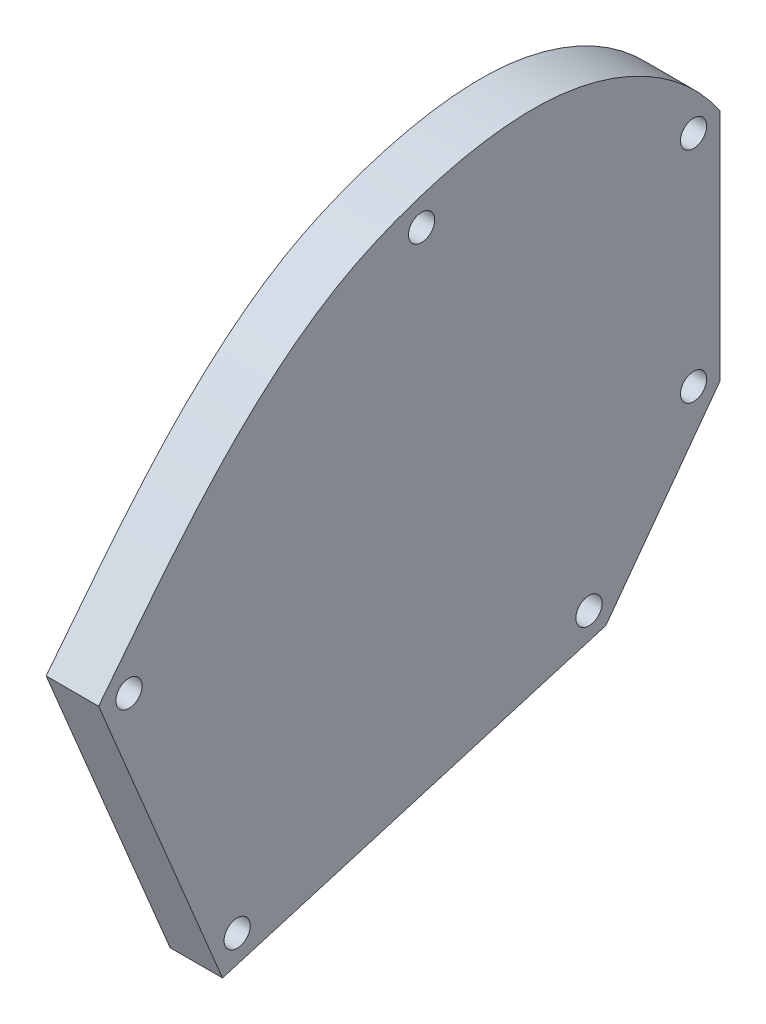
SolidWorks part; units mm, degrees
ref_plane "Front Plane" through (0, 0, 0) normal (0, 0, 1) x (1, 0, 0)
ref_plane "Top Plane" through (0, 0, 0) normal (0, 1, 0) x (1, 0, 0)
ref_plane "Right Plane" through (0, 0, 0) normal (1, 0, 0) x (0, 0, -1)
sketch "Sketch1" plane through (0, 0, 0) normal (1, 0, 0) x (0, 0, -1)
  line L0 (-30.0908, -0.204) -> (-18.0855, -29.0084)
  line L1 (-18.0855, -29.0084) -> (19.0458, -18.0105)
  line L2 (19.0458, -18.0105) -> (30.0908, -3.0459)
  line L3 (30.0908, -3.0459) -> (30.0908, 19.6501)
  spline S0 degree 3 poles (30.0908, 19.6501) (28.0376, 22.7267) (23.0332, 26.8607) (14.9878, 29.0084) (7.5247, 28.7742) (0.6039, 27.0366) (-6.7277, 23.8999) (-13.0411, 19.3751) (-21.1986, 11.3805) (-26.4061, 4.431) (-30.0908, -0.204) knots 0 0 0 0 0.148847 0.252988 0.329376 0.448669 0.539169 0.650373 0.760197 1 1 1 1
extrude "Boss-Extrude1" add sketch "Sketch1" along normal blind 5.08
sketch "Sketch2" plane through (5.08, 0, 0) normal (1, 0, 0) x (0, 0, -1)
  circle A0 centre (-27.1491, -0.59) radius 1.27
  circle A1 centre (-16.6658, -25.9503) radius 1.27
  circle A2 centre (17.4122, -15.9375) radius 1.27
  circle A3 centre (27.5449, -2.2002) radius 1.27
  circle A4 centre (27.5449, 19.0422) radius 1.27
  circle A5 centre (1.1987, 24.3199) radius 1.27
  point P12 (-26.8987, -0.1896)
  point P13 (-27.3003, -0.6502)
  point P14 (-16.6658, -25.9503)
  point P15 (17.156, -15.7697)
  point P16 (0, 0)
  point P17 (0, 0)
  point P18 (0, 0)
  point P19 (-27.1491, -0.59)
  point P20 (17.4122, -15.9375)
  point P21 (27.5449, -2.2002)
  point P22 (17.262, -15.911)
  point P23 (28.0869, 19.1971)
  point P24 (1.1425, 24.4884)
  point P25 (1.1987, 24.3199)
  point P26 (27.3675, -2.215)
  point P27 (27.5449, 19.0422)
  dimension "D1" = 2.54
  dimension "D2" = 2.54
  dimension "D3" = 2.54
  dimension "D4" = 2.54
  dimension "D5" = 2.54
  dimension "D6" = 2.54
extrude "Cut-Extrude1" cut sketch "Sketch2" against normal blind 10
